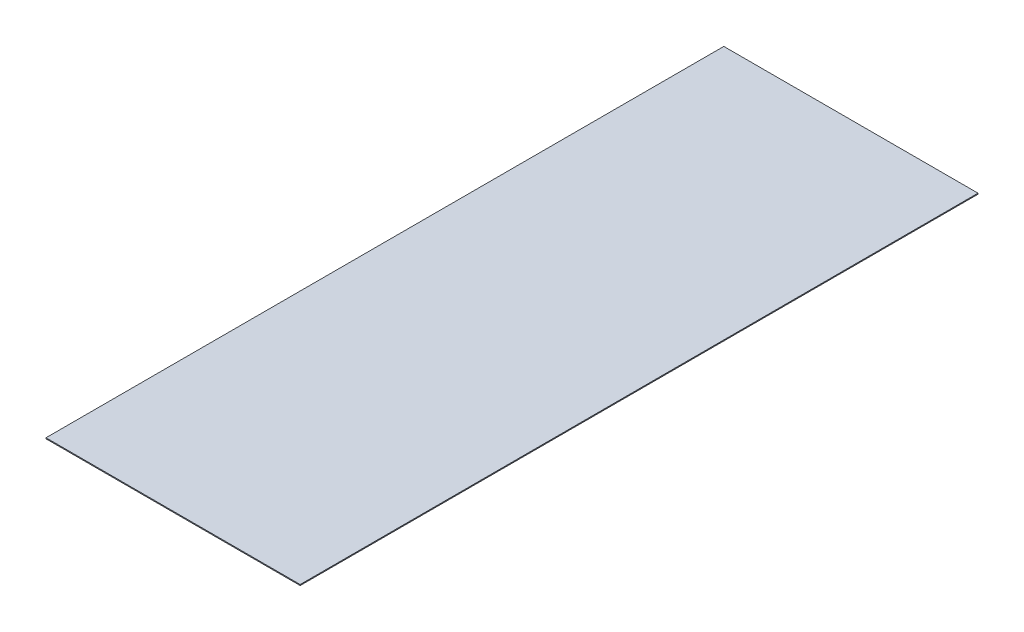
SolidWorks part; units mm, degrees
material "ASTM A36 Acero"
ref_plane "Alzado" through (0, 0, 0) normal (0, 0, 1) x (1, 0, 0)
ref_plane "Planta" through (0, 0, 0) normal (0, 1, 0) x (1, 0, 0)
ref_plane "Vista lateral" through (0, 0, 0) normal (1, 0, 0) x (0, 0, -1)
sketch "Croquis1" plane through (0, 0, 0) normal (0, 1, 0) x (1, 0, 0)
  line L1 (-457.2, -1219.2) -> (457.2, -1219.2)
  line L2 (-457.2, -1219.2) -> (-457.2, 1219.2)
  line L3 (-457.2, 1219.2) -> (457.2, 1219.2)
  line L4 (457.2, -1219.2) -> (457.2, 1219.2)
  line L5 (-457.2, -1219.2) -> (457.2, 1219.2) construction
  line L6 (-457.2, 1219.2) -> (457.2, -1219.2) construction
  point P0 (0, 0)
  dimension "D1" = 2438.4
  dimension "D2" = 914.4
extrude "Saliente-Extruir1" add sketch "Croquis1" along normal blind 3.4
